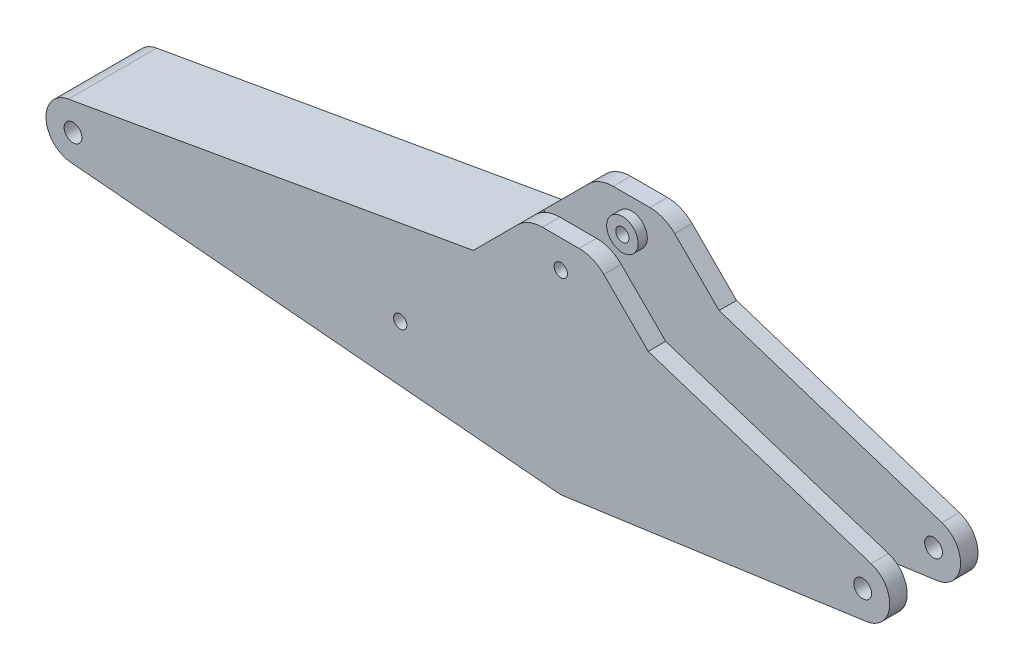
SolidWorks part; units mm, degrees
ref_plane "Front Plane" through (0, 0, 0) normal (0, 0, 1) x (1, 0, 0)
ref_plane "Top Plane" through (0, 0, 0) normal (0, 1, 0) x (1, 0, 0)
ref_plane "Right Plane" through (0, 0, 0) normal (1, 0, 0) x (0, 0, -1)
sketch "Sketch1" plane through (0, 0, 0) normal (0, 0, 1) x (1, 0, 0)
  line L0 (0, 0) -> (4525, 0) construction
  line L1 (2795, 875) -> (2795, -400) construction
  line L2 (-26.9221, 152.644) -> (2293.7016, 561.9365)
  line L3 (2293.7016, 561.9365) -> (2548.1864, 816.4214)
  line L4 (2689.6078, 875) -> (2900.3922, 875)
  line L5 (3041.8136, 816.4214) -> (3296.2984, 561.9365)
  line L6 (3296.2984, 561.9365) -> (4572.8695, 147.4229)
  line L7 (4546.6011, -153.4874) -> (2795, -400)
  line L8 (2795, -400) -> (-13.5024, -154.4108)
  line L9 (2293.7016, 561.9365) -> (3296.2984, 561.9365)
  arc A0 (-26.9221, 152.644) -> (-13.5024, -154.4108) centre (0, 0) ccw
  circle A1 centre (0, 0) radius 51
  arc A2 (4546.6011, -153.4874) -> (4572.8695, 147.4229) centre (4525, 0) ccw
  circle A3 centre (4525, 0) radius 51
  circle A4 centre (1875, 0) radius 38
  circle A8 centre (2795, 714.9365) radius 38
  arc A9 (2689.6078, 875) -> (2548.1864, 816.4214) centre (2689.6078, 675) ccw
  arc A10 (2900.3922, 875) -> (3041.8136, 816.4214) centre (2900.3922, 675) cw
  point P25 (2606.7651, 875)
  point P28 (2983.2349, 875)
  dimension "D5" = 102
  dimension "D6" = 310
  dimension "D12" = 76
  dimension "D14" = 153
  dimension "D15" = 200
  dimension "D16" = 200
  dimension "D1" = 4525
  dimension "D2" = 875
  dimension "D3" = 400
  dimension "D4" = 2795
  dimension "D7" = 45
  dimension "D8" = 45
  dimension "D9" = 15
  dimension "D10" = 26
  dimension "D11" = 2650
extrude "Boss-Extrude2" add sketch "Sketch1" against normal blind 100 contours L7 A2 L6 L9 L2 A0 L8 A4 A3 A1 | A10 L4 A9 L3 L9 L5 A8
sketch "Sketch4" plane through (0, 0, 0) normal (0, 0, 1) x (1, 0, 0)
  line L0 (2795, -400) -> (-13.5024, -154.4108) construction
  line L1 (-26.9221, 152.644) -> (2293.7016, 561.9365) construction
  line L2 (2795, -400) -> (-13.5024, -154.4108)
  line L3 (-26.9221, 152.644) -> (2293.7016, 561.9365)
  line L4 (2793.9414, -359.7548) -> (-10.0179, -114.5628)
  line L5 (-19.9745, 113.252) -> (2300.6492, 522.5445)
  line L6 (2798.4845, -360.1521) -> (-10.0179, -114.5628) construction
  line L7 (4546.6011, -153.4874) -> (2795, -400) construction
  line L8 (3819, -255.8868) -> (2795, -400)
  line L9 (3813.4255, -216.2771) -> (2793.9414, -359.7548)
  line L10 (3813.4255, -216.2771) -> (3819, -255.8868)
  line L11 (3813.4255, -216.2771) -> (2789.4255, -360.3903) construction
  line L12 (2293.7016, 561.9365) -> (2300.6492, 522.5445)
  arc A0 (-26.9221, 152.644) -> (-13.5024, -154.4108) centre (0, 0) ccw construction
  arc A1 (-26.9221, 152.644) -> (-13.5024, -154.4108) centre (0, 0) ccw
  arc A2 (-19.9745, 113.252) -> (-10.0179, -114.5628) centre (0, 0) ccw
  circle A3 centre (4525, 0) radius 51 construction
  dimension "D3" = 706
  dimension "D1" = 40
  dimension "D2" = 40
extrude "Boss-Extrude4" add sketch "Sketch4" along normal blind 306
sketch "Sketch7" plane through (0, 0, 0) normal (0, 0, 1) x (1, 0, 0)
  circle A0 centre (1875, 0) radius 38 construction
  circle A1 centre (2795, 714.9365) radius 38 construction
  circle A2 centre (1875, 0) radius 38
  circle A3 centre (2795, 714.9365) radius 38
  circle A4 centre (2795, 714.9365) radius 90
  circle A5 centre (1875, 0) radius 90
  dimension "D1" = 180
extrude "Boss-Extrude5" add sketch "Sketch7" along normal blind 53
ref_plane "Plane1" through (0, 0, 153) normal (0, 0, 1) x (1, 0, 0)
mirror "Mirror2" about plane through (0, 0, 153) normal (0, 0, 1) of "Boss-Extrude5", "Boss-Extrude2"
